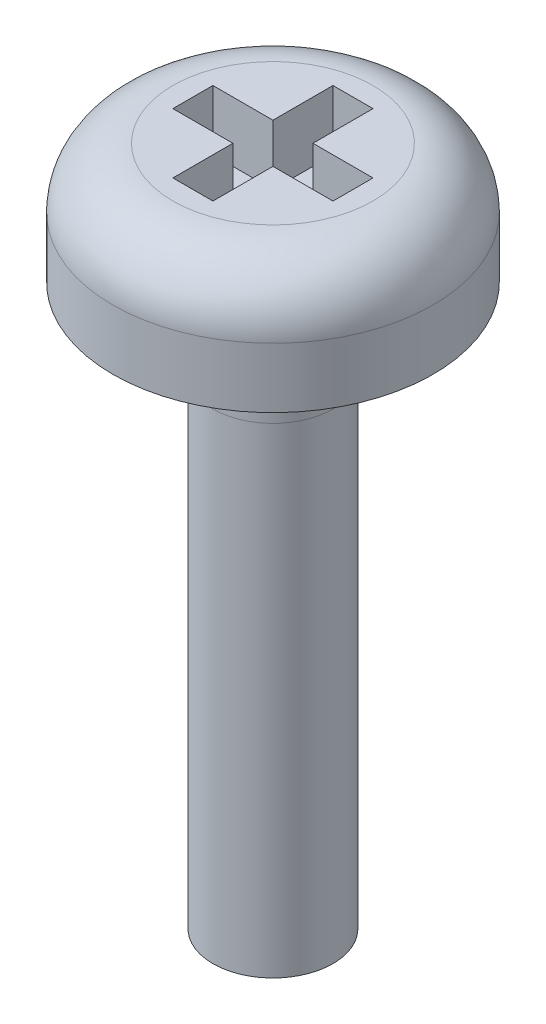
SolidWorks part; units mm, degrees
ref_plane "Front Plane" through (0, 0, 0) normal (0, 0, 1) x (1, 0, 0)
ref_plane "Top Plane" through (0, 0, 0) normal (0, 1, 0) x (1, 0, 0)
ref_plane "Right Plane" through (0, 0, 0) normal (1, 0, 0) x (0, 0, -1)
sketch "Sketch3" plane through (0, 0, 0) normal (0, 1, 0) x (1, 0, 0)
  circle A0 centre (0, 0) radius 0.75
  dimension "D1" = 1.5
extrude "Boss-Extrude1" add sketch "Sketch3" along normal blind 7
sketch "Sketch4" plane through (0, 7, 0) normal (0, 1, 0) x (1, 0, 0)
  circle A0 centre (0, 0) radius 2
  dimension "D1" = 4
extrude "Boss-Extrude2" add sketch "Sketch4" along normal blind 1.5
fillet "Fillet3" radius 0.75 1 edges at (0, 8.5, 2)
sketch "Sketch6" plane through (0, 8.5, 0) normal (0, 1, 0) x (1, 0, 0)
  line L5 (0.25, 0.25) -> (1, 0.25)
  line L6 (-0.25, 1) -> (0.25, 1)
  line L11 (-0.25, 1) -> (-0.25, 0.25)
  line L12 (-0.25, -1) -> (0.25, -1)
  line L13 (0.25, 1) -> (0.25, 0.25)
  line L18 (-1, 0.25) -> (-0.25, 0.25)
  line L20 (-1, 0.25) -> (-1, -0.25)
  line L21 (-1, -0.25) -> (-0.25, -0.25)
  line L22 (1, 0.25) -> (1, -0.25)
  line L28 (0.25, -0.25) -> (1, -0.25)
  line L29 (0.25, -0.25) -> (0.25, -1)
  line L30 (-0.25, -0.25) -> (-0.25, -1)
  point P0 (0, 0)
  point P6 (0, 0)
  dimension "D1" = 0.5
  dimension "D2" = 0.5
  dimension "D3" = 2
  dimension "D4" = 2
extrude "Cut-Extrude4" cut sketch "Sketch6" against normal blind 0.75
sketch "Sketch7" plane through (0, 0, 0) normal (0, 0, 1) x (1, 0, 0)
  line L0 (-7.4335, 6) -> (10.8456, 6)
  dimension "D1" = 6
split line "Split Line1"
